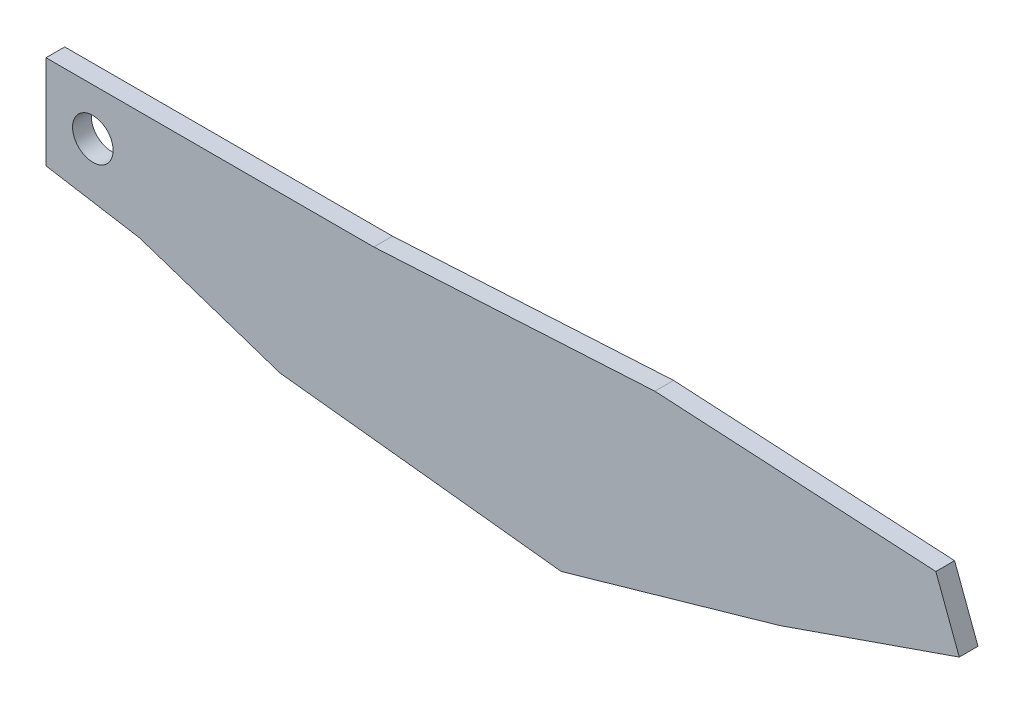
SolidWorks part; units mm, degrees
ref_plane "前视基准面" through (0, 0, 0) normal (0, 0, 1) x (1, 0, 0)
ref_plane "上视基准面" through (0, 0, 0) normal (0, 1, 0) x (1, 0, 0)
ref_plane "右视基准面" through (0, 0, 0) normal (1, 0, 0) x (0, 0, -1)
other "Configuration Table"
sketch "草图1" plane through (0, 0, 0) normal (0, 0, 1) x (1, 0, 0)
  line L0 (-3, -3) -> (3, -4)
  line L1 (3, -4) -> (12, -7)
  line L2 (12, -7) -> (30, -9)
  line L3 (30, -9) -> (44, -5)
  line L4 (44, -5) -> (55.5, -1)
  line L5 (55.5, -1) -> (54, 3)
  line L6 (54, 3) -> (36, 4)
  line L7 (36, 4) -> (18, 3)
  line L8 (18, 3) -> (4, 3)
  line L9 (4, 3) -> (-3, 3)
  line L10 (-3, 3) -> (-3, -3)
  circle A0 centre (0, 0) radius 1.3
extrude "柔性桨叶包络_展开总径127" add sketch "草图1" along normal blind 1.2
